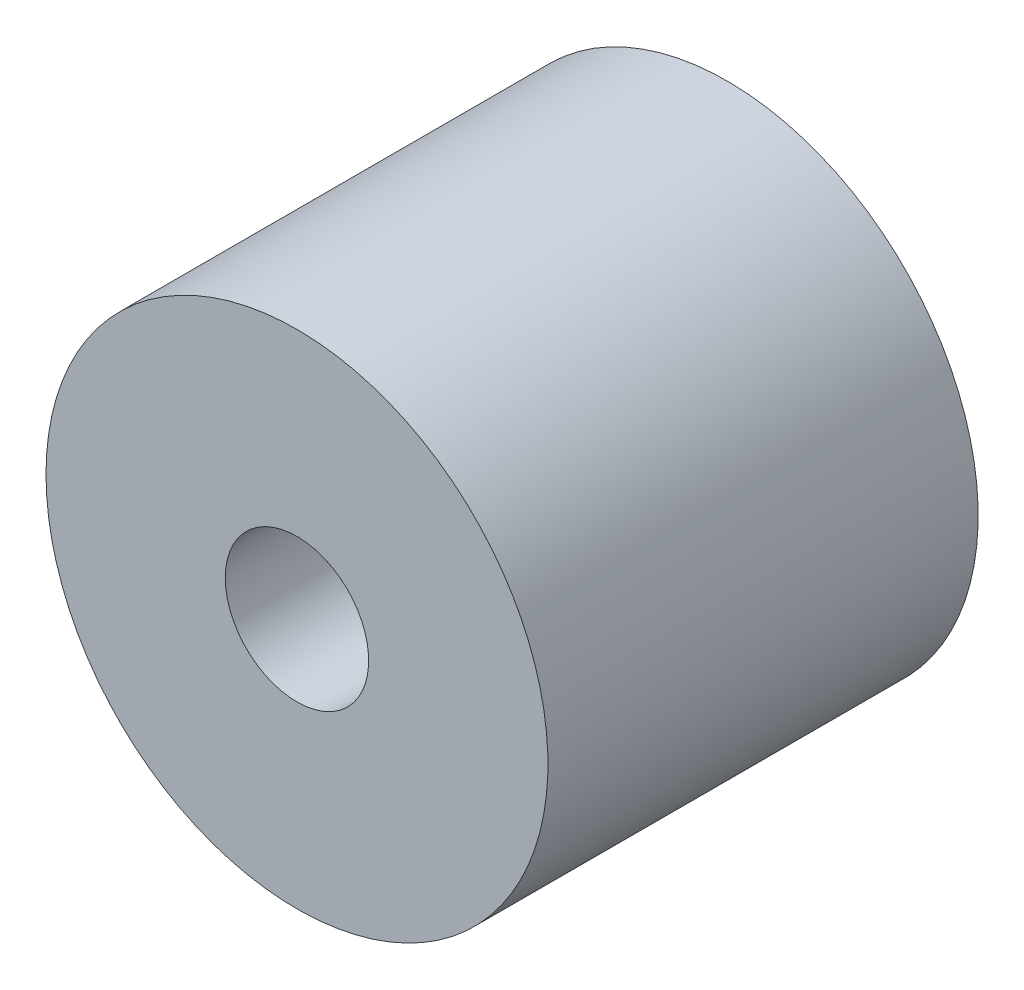
SolidWorks part; units mm, degrees
ref_plane "Front Plane" through (0, 0, 0) normal (0, 0, 1) x (1, 0, 0)
ref_plane "Top Plane" through (0, 0, 0) normal (0, 1, 0) x (1, 0, 0)
ref_plane "Right Plane" through (0, 0, 0) normal (1, 0, 0) x (0, 0, -1)
sketch "AnnulusProfile" plane through (0, 0, 0) normal (0, 1, 0) x (1, 0, 0)
  line L1 (2, 0) -> (7, 0)
  line L2 (2, 0) -> (2, -12)
  line L3 (2, -12) -> (7, -12)
  line L4 (7, 0) -> (7, -12)
  line L5 (0, 0) -> (0, -20) construction
  dimension "inner_radius_mm" = 2
  dimension "outer_radius_mm" = 7
  dimension "height_mm" = 12
revolve "Revolution" add sketch "AnnulusProfile" angle 360 about L5
